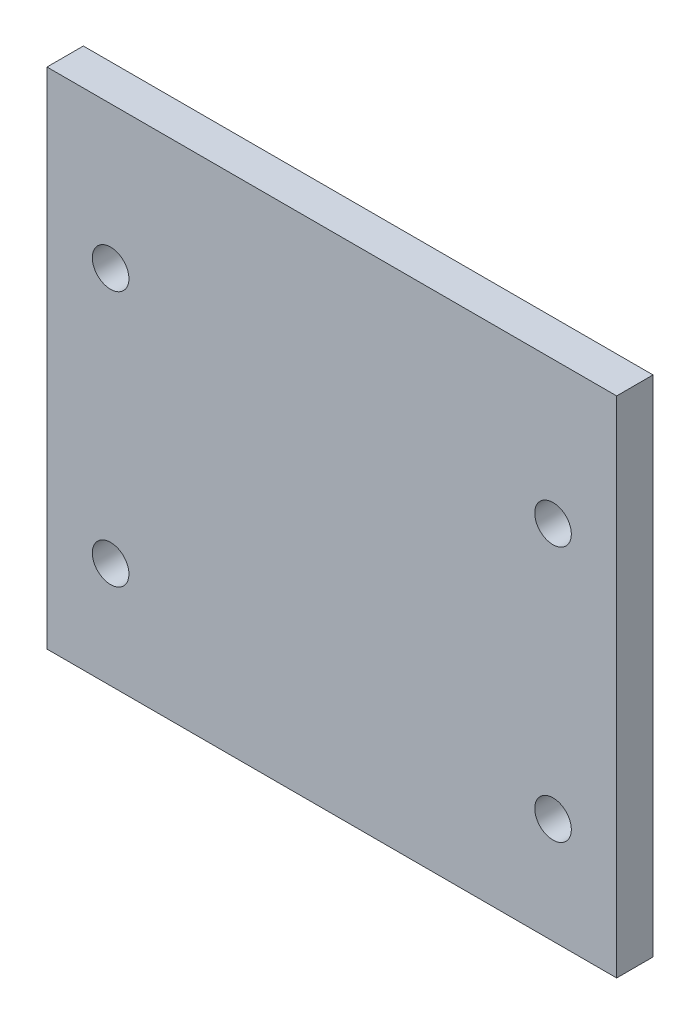
SolidWorks part; units mm, degrees
ref_plane "Front Plane" through (0, 0, 0) normal (0, 0, 1) x (1, 0, 0)
ref_plane "Top Plane" through (0, 0, 0) normal (0, 1, 0) x (1, 0, 0)
ref_plane "Right Plane" through (0, 0, 0) normal (1, 0, 0) x (0, 0, -1)
sketch "Sketch1" plane through (0, 0, 0) normal (0, 0, 1) x (1, 0, 0)
  line L1 (0, 0) -> (47, 0)
  line L2 (0, 0) -> (0, 41.59)
  line L3 (0, 41.59) -> (47, 41.59)
  line L4 (47, 0) -> (47, 41.59)
  circle A0 centre (5.25, 8.74) radius 1.51
  circle A1 centre (41.75, 8.74) radius 1.51
  circle A2 centre (41.75, 29.84) radius 1.51
  circle A3 centre (5.25, 29.84) radius 1.51
  dimension "D3" = 3.02
  dimension "D4" = 3.02
  dimension "D5" = 3.02
  dimension "D6" = 3.02
  dimension "D7" = 5.25
  dimension "D9" = 8.74
  dimension "D10" = 8.74
  dimension "D11" = 5.25
  dimension "D12" = 5.25
  dimension "D13" = 11.75
  dimension "D14" = 11.75
  dimension "D1" = 47
  dimension "D2" = 41.59
  dimension "D8" = 5.25
extrude "Boss-Extrude1" add sketch "Sketch1" along normal blind 3
